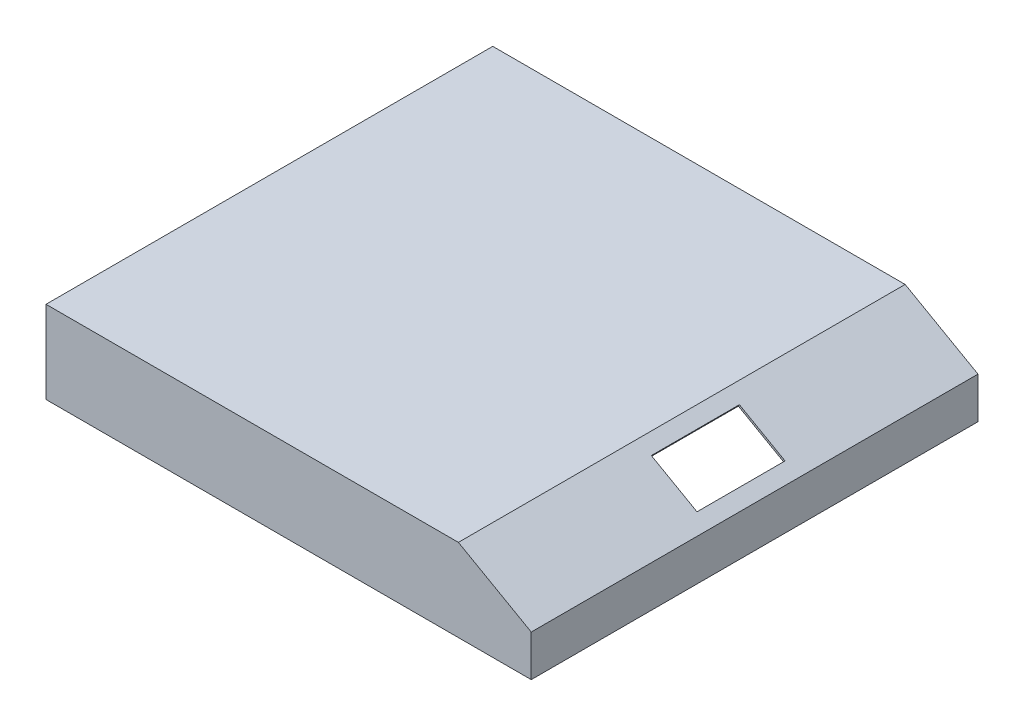
SolidWorks part; units mm, degrees
ref_plane "Alzado" through (0, 0, 0) normal (0, 0, 1) x (1, 0, 0)
ref_plane "Planta" through (0, 0, 0) normal (0, 1, 0) x (1, 0, 0)
ref_plane "Vista lateral" through (0, 0, 0) normal (1, 0, 0) x (0, 0, -1)
sketch "Croquis1" plane through (0, 0, 0) normal (0, 0, 1) x (1, 0, 0)
  line L0 (0, 0) -> (0, 120)
  line L1 (0, 120) -> (600, 120)
  line L2 (600, 120) -> (705.9851, 60)
  line L3 (705.9851, 60) -> (705.9851, 0)
  line L4 (705.9851, 0) -> (0, 0)
extrude "Saliente-Extruir1" add sketch "Croquis1" along normal mid plane 650
shell "Vaciado1" thickness 3
sketch "Croquis2" plane through (197.069, 348.1062, 0) normal (0.4927, 0.8702, 0) x (0.8702, -0.4927, 0)
  line L1 (485.7227, 64.0782) -> (562.1039, 64.0782)
  line L2 (485.7227, 64.0782) -> (485.7227, -64.0782)
  line L3 (485.7227, -64.0782) -> (562.1039, -64.0782)
  line L4 (562.1039, 64.0782) -> (562.1039, -64.0782)
  line L5 (485.7227, 64.0782) -> (562.1039, -64.0782) construction
  line L6 (485.7227, -64.0782) -> (562.1039, 64.0782) construction
  point P0 (523.9133, 0)
  dimension "D1" = 128.1565
  dimension "D2" = 76.3812
extrude "Cortar-Extruir1" cut sketch "Croquis2" against normal through all
